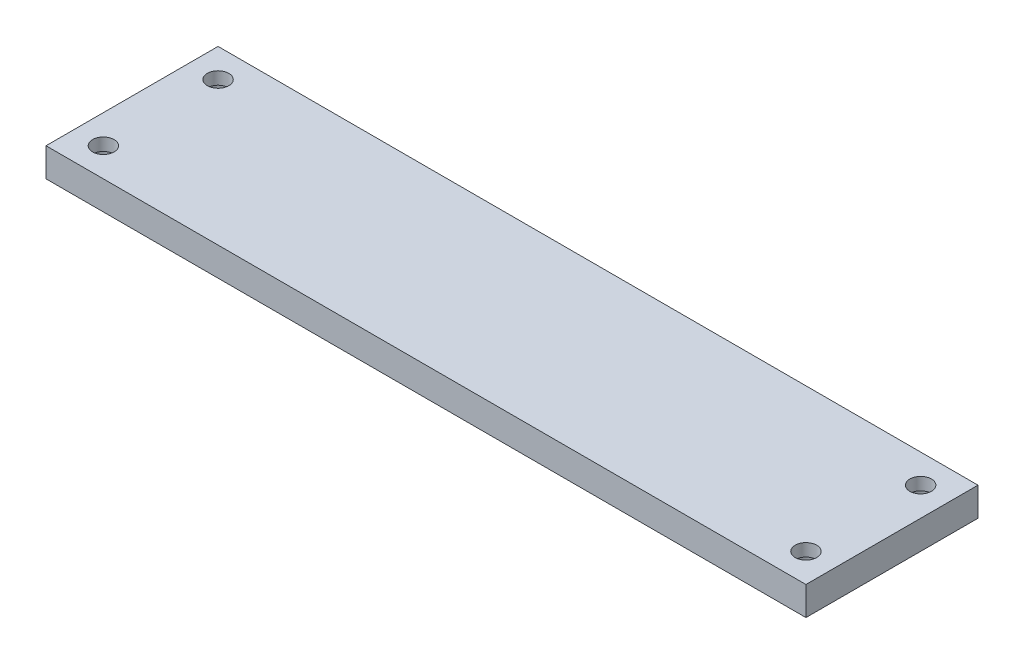
SolidWorks part; units mm, degrees
material "ABS"
ref_plane "Alzado" through (0, 0, 0) normal (0, 0, 1) x (1, 0, 0)
ref_plane "Planta" through (0, 0, 0) normal (0, 1, 0) x (1, 0, 0)
ref_plane "Vista lateral" through (0, 0, 0) normal (1, 0, 0) x (0, 0, -1)
sketch "Croquis1" plane through (0, 0, 0) normal (0, 1, 0) x (1, 0, 0)
  line L1 (54, -13) -> (-54, -13)
  line L2 (54, -13) -> (54, 13)
  line L3 (54, 13) -> (-54, 13)
  line L4 (-54, -13) -> (-54, 13)
  line L5 (54, -13) -> (-54, 13) construction
  line L6 (54, 13) -> (-54, -13) construction
  point P0 (0, 0)
  dimension "D1" = 26
  dimension "D2" = 108
extrude "Saliente-Extruir2" add sketch "Croquis1" along normal blind 2
sketch "Croquis3" plane through (0, 2, 0) normal (0, 1, 0) x (1, 0, 0)
  line L0 (-54, 13) -> (-54, -13) construction
  line L1 (52, -11) -> (-52, -11)
  line L2 (52, -11) -> (52, 11)
  line L3 (52, 11) -> (-52, 11)
  line L4 (-52, -11) -> (-52, 11)
  line L5 (52, -11) -> (-52, 11) construction
  line L6 (52, 11) -> (-52, -11) construction
  line L7 (54, 13) -> (-54, 13) construction
  line L8 (0, 11) -> (0, 8.9513)
  line L9 (0, 0) -> (-11.0205, 0)
  circle A0 centre (-49, 8) radius 1.5
  circle A1 centre (-49, -8) radius 1.5
  circle A2 centre (49, 8) radius 1.5
  circle A3 centre (49, -8) radius 1.5
  point P0 (0, 0)
  dimension "D3" = 3
  dimension "D1" = 2
  dimension "D2" = 2
  dimension "D4" = 3
extrude "Cortar-Extruir3" cut sketch "Croquis3" against normal blind 10 contours A0 | A1 | A3 | A2
sketch "Croquis5" plane through (0, 0, 0) normal (0, -1, 0) x (1, 0, 0)
  line L1 (54, 13) -> (-54, 13)
  line L2 (54, 13) -> (54, -13)
  line L3 (54, -13) -> (-54, -13)
  line L4 (-54, 13) -> (-54, -13)
  line L5 (54, 13) -> (-54, -13) construction
  line L6 (54, -13) -> (-54, 13) construction
  circle A0 centre (-49, -8) radius 1.5
  circle A1 centre (-49, 8) radius 1.5
  circle A2 centre (49, 8) radius 1.5
  circle A3 centre (49, -8) radius 1.5
  point P0 (0, 0)
extrude "Saliente-Extruir4" add sketch "Croquis5" along normal blind 2
sketch "Croquis6" plane through (0, -2, 0) normal (0, -1, 0) x (1, 0, 0)
  circle A0 centre (-49, -8) radius 2.5
  circle A1 centre (-49, 8) radius 2.5
  circle A2 centre (49, -8) radius 2.5
  circle A3 centre (49, 8) radius 2.5
extrude "Cortar-Extruir4" cut sketch "Croquis6" against normal blind 2.25
sketch "Croquis7" plane through (0, -2, 0) normal (0, -1, 0) x (1, 0, 0)
  line L1 (53, 12) -> (-53, 12)
  line L2 (53, 12) -> (53, -12)
  line L3 (53, -12) -> (-53, -12)
  line L4 (-53, 12) -> (-53, -12)
  line L5 (53, 12) -> (-53, -12) construction
  line L6 (53, -12) -> (-53, 12) construction
  line L7 (54, 13) -> (-54, 13)
  line L8 (54, 13) -> (54, -13)
  line L9 (54, -13) -> (-54, -13)
  line L10 (-54, 13) -> (-54, -13)
  line L11 (54, 13) -> (-54, -13) construction
  line L12 (54, -13) -> (-54, 13) construction
  point P0 (0, 0)
  point P6 (0, 0)
  dimension "D1" = 106
  dimension "D2" = 24
extrude "Cortar-Extruir5" cut sketch "Croquis7" against normal blind 19
